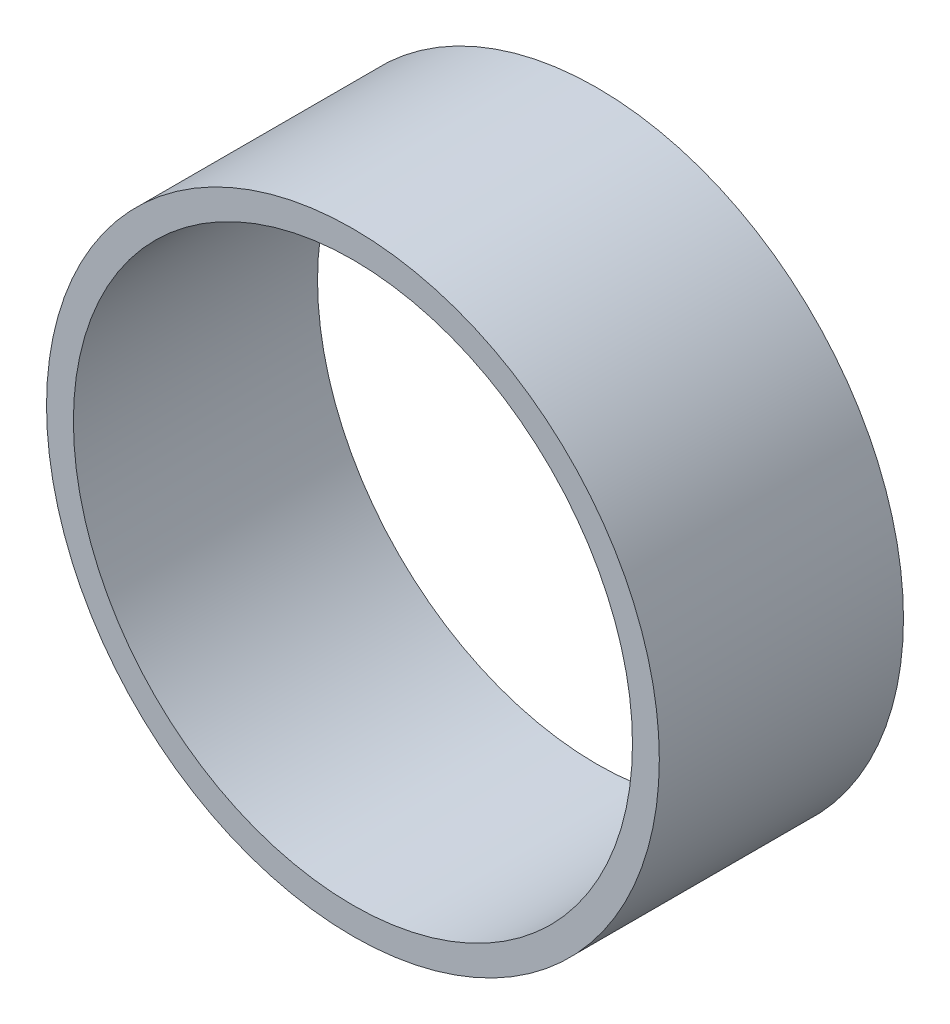
SolidWorks part; units mm, degrees
material "Wildman Fiberglass"
ref_plane "Front Plane" through (0, 0, 0) normal (0, 0, 1) x (1, 0, 0)
ref_plane "Top Plane" through (0, 0, 0) normal (0, 1, 0) x (1, 0, 0)
ref_plane "Right Plane" through (0, 0, 0) normal (1, 0, 0) x (0, 0, -1)
sketch "Sketch1" plane through (0, 0, 0) normal (0, 0, 1) x (1, 0, 0)
  circle A0 centre (0, 0) radius 15.9385
  circle A1 centre (0, 0) radius 14.5415
  dimension "D1" = 31.877
  dimension "D2" = 29.083
extrude "Boss-Extrude1" add sketch "Sketch1" along normal mid plane 12.7
